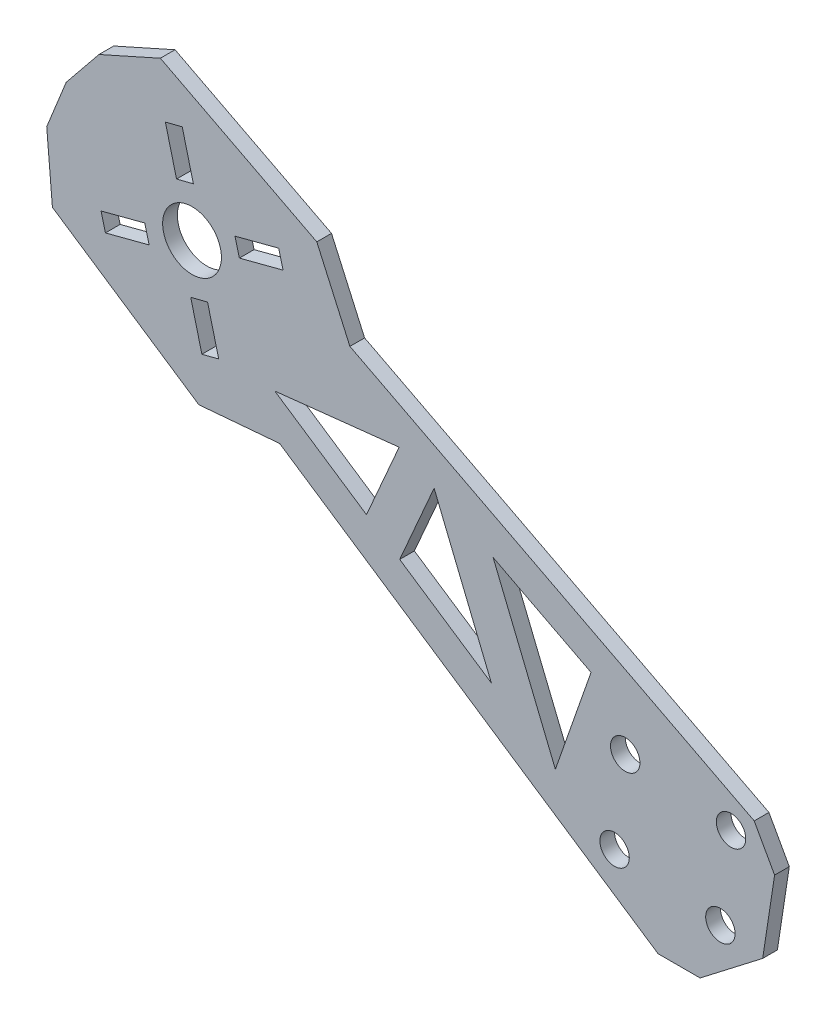
SolidWorks part; units mm, degrees
ref_plane "Front Plane" through (0, 0, 0) normal (0, 0, 1) x (1, 0, 0)
ref_plane "Top Plane" through (0, 0, 0) normal (0, 1, 0) x (1, 0, 0)
ref_plane "Right Plane" through (0, 0, 0) normal (1, 0, 0) x (0, 0, -1)
sketch "Sketch1" plane through (0, 0, 0) normal (0, 0, 1) x (1, 0, 0)
  line L0 (169.4354, 243.2996) -> (852.102, 243.2996) construction
  line L1 (-12.6917, 68.059) -> (-107.4521, 123.9201) construction
  line L2 (-12.6917, 68.059) -> (-21.2061, 61.4972)
  line L3 (-21.2061, 61.4972) -> (-26.9259, 61.4972)
  line L4 (-26.9259, 61.4972) -> (-78.4168, 95.876)
  line L5 (-78.4168, 95.876) -> (-89.4058, 94.9409)
  line L6 (-89.4058, 94.9409) -> (-109.3306, 108.2441)
  line L7 (-161.7244, -138.6454) -> (118.2756, -138.6454) construction
  line L8 (-161.7244, -138.6454) -> (-161.7244, 141.3546) construction
  line L9 (-257.6237, -730.0336) -> (-1294.9545, -912.943) construction
  line L10 (-109.3306, 108.2441) -> (-110.1063, 117.3597)
  line L11 (-110.1063, 117.3597) -> (-107.4521, 123.9201)
  line L12 (-102.716, 111.1222) -> (-96.7719, 112.6762)
  line L13 (-102.716, 111.1222) -> (-102.1181, 108.8353)
  line L14 (-96.7719, 112.6762) -> (-96.174, 110.3892)
  line L15 (-102.1181, 108.8353) -> (-96.174, 110.3892)
  line L16 (-92.3641, 110.3825) -> (-88.3015, 117.2742) construction
  line L17 (-91.6708, 126.5576) -> (-90.1522, 120.6043)
  line L18 (-92.4427, 120.02) -> (-90.1522, 120.6043)
  line L19 (-93.9613, 125.9733) -> (-91.6708, 126.5576)
  line L20 (-93.9613, 125.9733) -> (-92.4427, 120.02)
  line L21 (-102.9973, 129.4191) -> (-107.4521, 123.9201)
  line L22 (-94.646, 133.1544) -> (-102.9973, 129.4191)
  line L23 (-73.3584, 122.1629) -> (-94.646, 133.1544)
  line L24 (-68.8555, 112.0953) -> (-73.3584, 122.1629)
  line L25 (-13.8429, 83.6905) -> (-68.8555, 112.0953)
  line L26 (-11.0733, 78.686) -> (-13.8429, 83.6905)
  line L27 (-12.6917, 68.059) -> (-11.0733, 78.686)
  line L28 (-77.9497, 116.5345) -> (-83.8938, 114.9805)
  line L29 (-77.9497, 116.5345) -> (-78.5476, 118.8214)
  line L30 (-78.5476, 118.8214) -> (-84.4917, 117.2674)
  line L31 (-83.8938, 114.9805) -> (-84.4917, 117.2674)
  line L32 (-88.223, 107.6367) -> (-90.5135, 107.0524)
  line L33 (-86.7044, 101.6834) -> (-88.223, 107.6367)
  line L34 (-86.7044, 101.6834) -> (-88.9949, 101.0991)
  line L35 (-88.9949, 101.0991) -> (-90.5135, 107.0524)
  line L63 (-31.394, 82.75) -> (-32.8423, 70.8377) construction
  line L64 (-18.4483, 69.0877) -> (-32.8423, 70.8377) construction
  line L65 (-17, 81) -> (-31.394, 82.75) construction
  line L66 (-17, 81) -> (-18.4483, 69.0877) construction
  circle A0 centre (-90.3328, 113.8283) radius 4
  circle A25 centre (-18.4483, 69.0877) radius 2
  circle A26 centre (-32.8423, 70.8377) radius 2
  circle A27 centre (-31.394, 82.75) radius 2
  circle A28 centre (-17, 81) radius 2
  dimension "D2" = 8
  dimension "D1" = 110
  dimension "D3" = 280
  dimension "D4" = 280
extrude "Boss-Extrude1" add sketch "Sketch1" along normal blind 2
sketch "Sketch5" plane through (0, 0, 0) normal (0, 0, -1) x (-1, 0, 0)
  line L0 (40.9006, 76.2385) -> (36.0433, 90.0888)
  line L1 (36.0433, 90.0888) -> (49.3715, 96.9706)
  line L2 (49.3715, 96.9706) -> (40.9006, 76.2385)
  line L3 (49.6065, 82.0512) -> (57.3952, 101.1135)
  line L4 (57.3952, 101.1135) -> (62.0815, 90.3803)
  line L5 (62.0815, 90.3803) -> (49.6065, 82.0512)
  line L6 (62.1535, 103.5704) -> (66.5964, 93.3947)
  line L7 (66.5964, 93.3947) -> (79.0714, 101.7239)
  line L8 (79.0714, 101.7239) -> (62.1535, 103.5704)
  line L9 (26.9259, 61.4972) -> (78.4168, 95.876) construction
  line L10 (13.8429, 83.6905) -> (68.8555, 112.0953) construction
  dimension "D1" = 4.5
  dimension "D2" = 4.5
  dimension "D3" = 4.5
  dimension "D4" = 4.5
  dimension "D5" = 4.5
  dimension "D6" = 4.5
  dimension "D7" = 15
  dimension "D8" = 15
  dimension "D9" = 15
extrude "Cut-Extrude1" cut sketch "Sketch5" against normal through all
